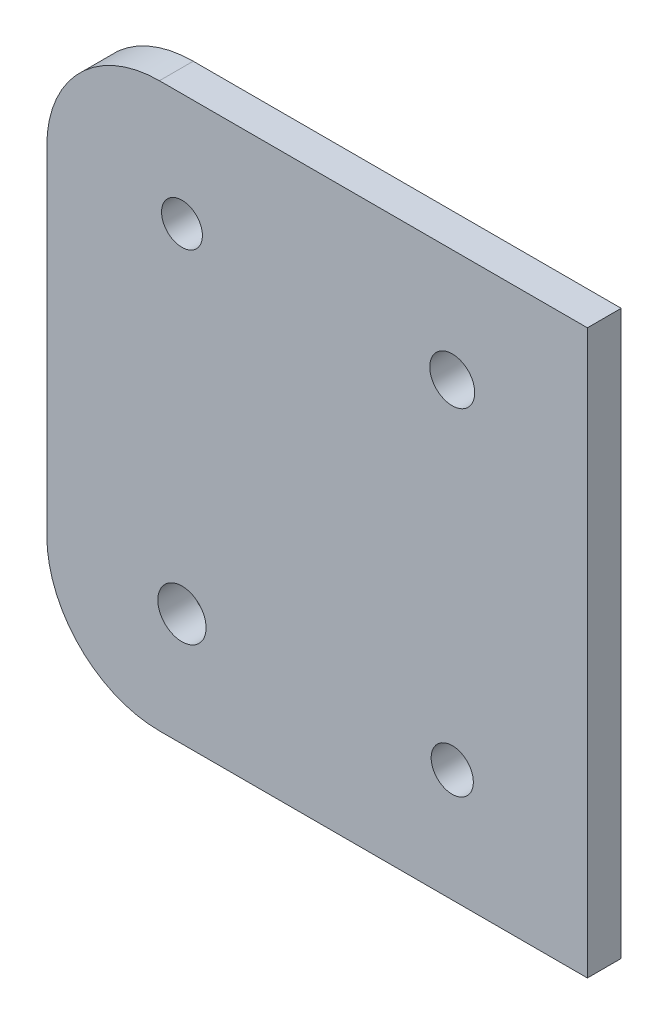
SolidWorks part; units mm, degrees
ref_plane "Front Plane" through (0, 0, 0) normal (0, 0, 1) x (1, 0, 0)
ref_plane "Top Plane" through (0, 0, 0) normal (0, 1, 0) x (1, 0, 0)
ref_plane "Right Plane" through (0, 0, 0) normal (1, 0, 0) x (0, 0, -1)
sketch "Sketch1" plane through (0, 0, 0) normal (0, 0, 1) x (1, 0, 0)
  line L1 (-13.3247, 14.6234) -> (24.6753, 14.6234)
  line L2 (-23.3247, 4.6234) -> (-23.3247, -25.3766)
  line L3 (-13.3247, -35.3766) -> (24.6753, -35.3766)
  line L4 (24.6753, 14.6234) -> (24.6753, -35.3766)
  circle A0 centre (-11.3247, 4.6234) radius 1.8145
  circle A1 centre (12.6753, 4.6234) radius 1.9958
  circle A2 centre (-11.3247, -25.3766) radius 2.1419
  circle A3 centre (12.6753, -25.3766) radius 1.873
  arc A4 (-23.3247, 4.6234) -> (-13.3247, 14.6234) centre (-13.3247, 4.6234) cw
  arc A5 (-13.3247, -35.3766) -> (-23.3247, -25.3766) centre (-13.3247, -25.3766) cw
  point P19 (5.6753, 14.6234)
  point P22 (-23.3247, -10.3766)
  dimension "D1" = 24
  dimension "D7" = 10
  dimension "D8" = 10
  dimension "D2" = 30
  dimension "D3" = 10
  dimension "D4" = 10
  dimension "D5" = 12
  dimension "D6" = 12
extrude "Boss-Extrude1" add sketch "Sketch1" along normal blind 3
